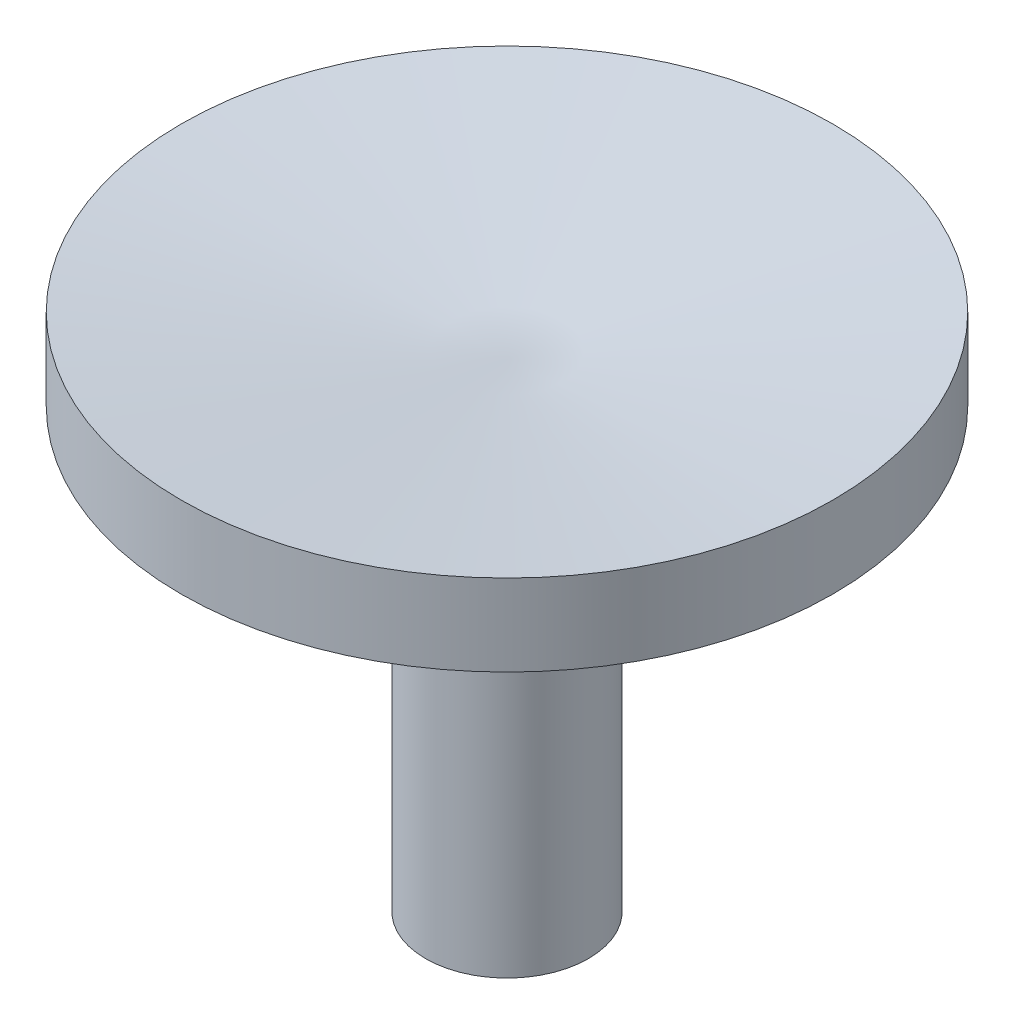
SolidWorks part; units mm, degrees
ref_plane "前视基准面" through (0, 0, 0) normal (0, 0, 1) x (1, 0, 0)
ref_plane "上视基准面" through (0, 0, 0) normal (0, 1, 0) x (1, 0, 0)
ref_plane "右视基准面" through (0, 0, 0) normal (1, 0, 0) x (0, 0, -1)
sketch "Sketch2" plane through (0, 0, 0) normal (0, 0, 1) x (1, 0, 0)
  line L0 (0, 0) -> (0, 0.875)
  line L1 (0, 0.875) -> (4, 1.375)
  line L2 (4, 1.375) -> (4, 0.375)
  line L3 (4, 0.375) -> (1, 0)
  line L4 (0, 0) -> (1, 0)
  dimension "D1" = 4
  dimension "D2" = 0.5
  dimension "D3" = 1
  dimension "D4" = 1
revolve "Revolve1" add sketch "Sketch2" angle 360 about L0
sketch "Sketch3" plane through (0, 0, 0) normal (0, -1, 0) x (1, 0, 0)
  circle A0 centre (0, 0) radius 1
extrude "Boss-Extrude1" add sketch "Sketch3" along normal blind 5
